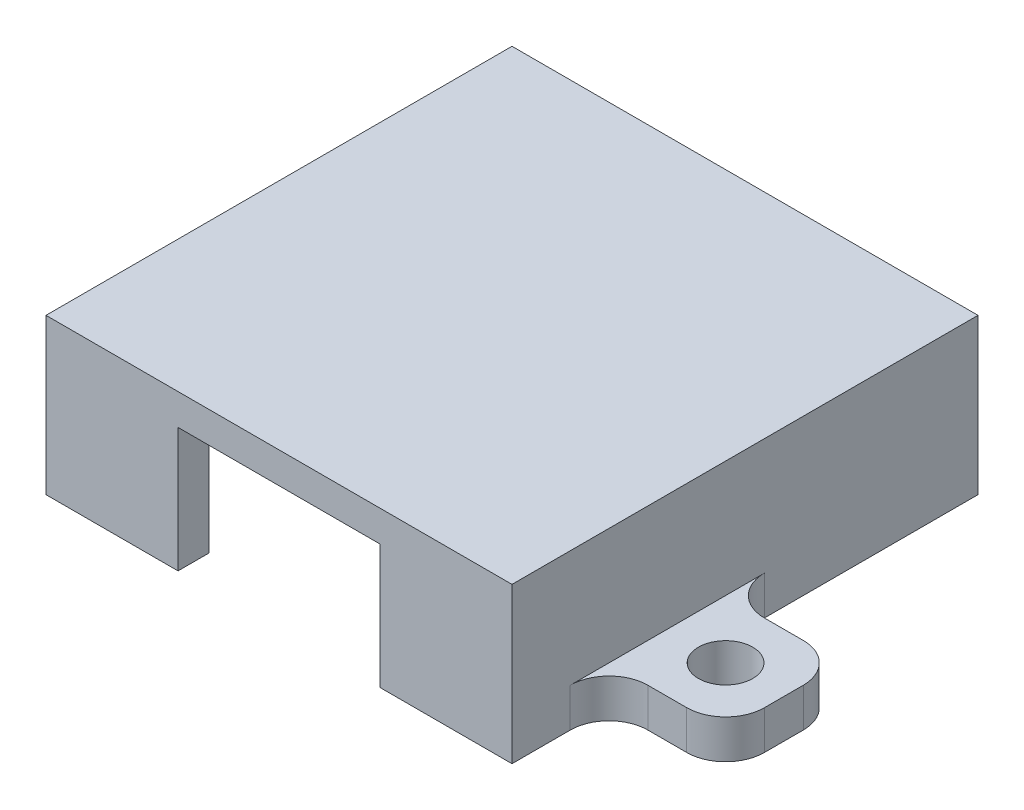
SolidWorks part; units mm, degrees
ref_plane "Front Plane" through (0, 0, 0) normal (0, 0, 1) x (1, 0, 0)
ref_plane "Top Plane" through (0, 0, 0) normal (0, 1, 0) x (1, 0, 0)
ref_plane "Right Plane" through (0, 0, 0) normal (1, 0, 0) x (0, 0, -1)
sketch "Sketch1" plane through (0, 0, 0) normal (0, 1, 0) x (1, 0, 0)
  line L1 (0, 0) -> (30, 0)
  line L2 (0, 0) -> (0, 30)
  line L3 (0, 30) -> (30, 30)
  line L4 (30, 0) -> (30, 30)
  dimension "D1" = 30
  dimension "D2" = 30
extrude "Boss-Extrude1" add sketch "Sketch1" along normal blind 10
sketch "Sketch2" plane through (0, 0, 0) normal (0, -1, 0) x (1, 0, 0)
  line L0 (8.5, 0) -> (21.5, 0)
  line L1 (0, 0) -> (30, 0) construction
  line L2 (21.5, 0) -> (21.5, -2)
  line L3 (21.5, -2) -> (28, -2)
  line L4 (28, -2) -> (28, -28)
  line L6 (2, -28) -> (2, -2)
  line L7 (2, -2) -> (8.5, -2)
  line L8 (8.5, -2) -> (8.5, 0)
  line L9 (30, 0) -> (30, -30) construction
  line L10 (0, -30) -> (0, 0) construction
  line L11 (30, -30) -> (0, -30) construction
  line L12 (2, -28) -> (2, -30)
  line L13 (2, -30) -> (8, -30)
  line L14 (8, -30) -> (8, -28)
  line L15 (8, -28) -> (22, -28)
  line L16 (22, -28) -> (22, -30)
  line L17 (22, -30) -> (28, -30)
  line L18 (28, -30) -> (28, -28)
  point P16 (15, 0)
  point P17 (15, -30)
  dimension "D1" = 13
  dimension "D2" = 2
  dimension "D3" = 2
  dimension "D4" = 2
  dimension "D5" = 2
  dimension "D6" = 6
extrude "Cut-Extrude1" cut sketch "Sketch2" against normal offset from surface (8 mm away) 2 up to face at (15, 10, -15)
sketch "Sketch3" plane through (0, 0, 0) normal (-1, 0, 0) x (0, 0, 1)
  line L0 (-30, 0) -> (0, 0) construction
  line L1 (-6.25, 0) -> (-13.75, 0)
  line L2 (-6.25, 0) -> (-6.25, 2.5)
  line L3 (-6.25, 2.5) -> (-13.75, 2.5)
  line L4 (-13.75, 0) -> (-13.75, 2.5)
  line L5 (0, 10) -> (0, 0) construction
  point P6 (-10, 2.5)
  dimension "D1" = 7.5
  dimension "D2" = 10
  dimension "D3" = 2.5
extrude "Boss-Extrude2" add sketch "Sketch3" along normal blind 7.5
sketch "Sketch4" plane through (0, 2.5, 0) normal (0, 1, 0) x (1, 0, 0)
  line L0 (-7.5, 13.75) -> (0, 13.75) construction
  line L1 (-7.5, 6.25) -> (-7.5, 13.75) construction
  circle A0 centre (-3.75, 10) radius 1.75
  point P2 (-3.75, 13.75)
  point P3 (-7.5, 10)
  point P6 (0, 0)
  point P9 (0, 0)
  dimension "D1" = 3.5
extrude "Cut-Extrude2" cut sketch "Sketch4" against normal through all
fillet "Fillet1" radius 2.5 4 edges at (0, 1.25, -6.25) (-7.5, 1.25, -6.25) (-7.5, 1.25, -13.75) (0, 1.25, -13.75)
ref_plane "Plane1" through (15, 0, 0) normal (-1, 0, 0) x (0, 0, 1)
mirror "Mirror1" about plane through (15, 0, 0) normal (-1, 0, 0) of "Boss-Extrude2", "Cut-Extrude2"
fillet "Fillet2" radius 2.5 4 edges at (37.5, 1.25, -13.75) (30, 1.25, -13.75) (37.5, 1.25, -6.25) (30, 1.25, -6.25)
